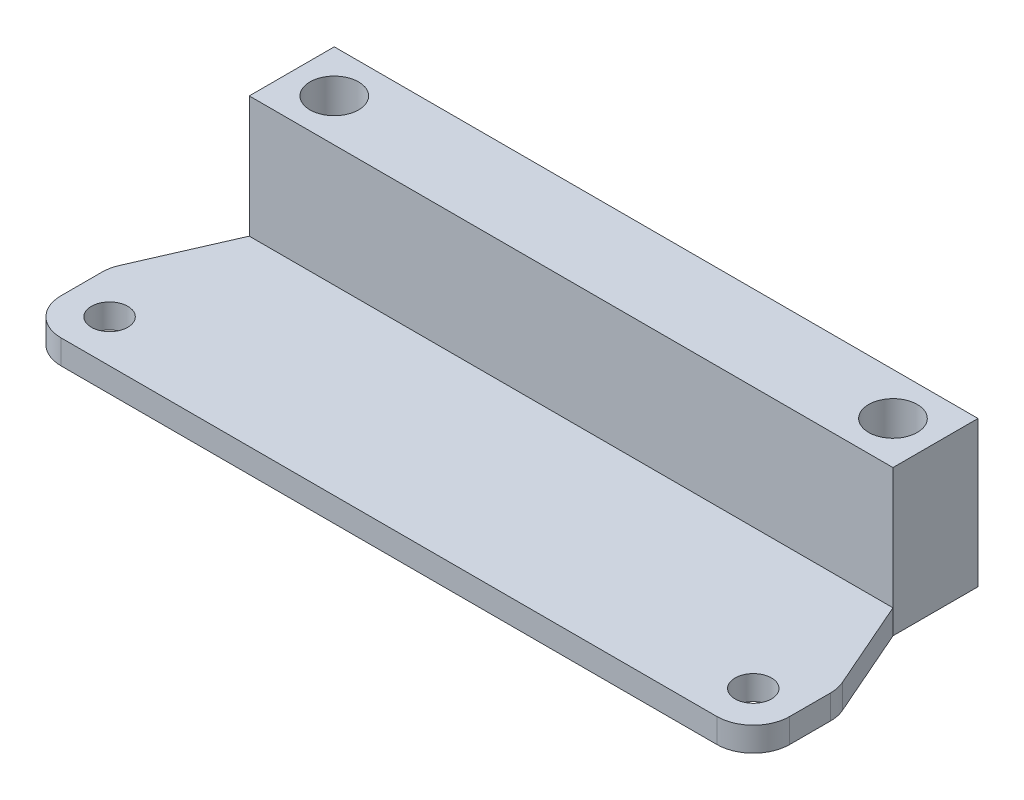
SolidWorks part; units mm, degrees
ref_plane "Front Plane" through (0, 0, 0) normal (0, 0, 1) x (1, 0, 0)
ref_plane "Top Plane" through (0, 0, 0) normal (0, 1, 0) x (1, 0, 0)
ref_plane "Right Plane" through (0, 0, 0) normal (1, 0, 0) x (0, 0, -1)
sketch "Sketch1" plane through (0, 0, 0) normal (0, 1, 0) x (1, 0, 0)
  line L0 (0.2515, 7.5749) -> (3.5, 15)
  line L17 (3.5, 15) -> (56.5, 15)
  line L18 (3.5, 15) -> (3.5, 22)
  line L19 (3.5, 22) -> (56.5, 22)
  line L20 (56.5, 15) -> (56.5, 22)
  line L21 (3, 0) -> (57, 0)
  line L22 (0, 3) -> (0, 6.3725)
  line L23 (0, 7) -> (60, 7)
  line L24 (60, 3) -> (60, 6.3725)
  line L25 (56.5, 15) -> (59.7485, 7.5749)
  arc A0 (60, 3) -> (57, 0) centre (57, 3) cw
  arc A1 (0, 3) -> (3, 0) centre (3, 3) ccw
  arc A2 (60, 6.3725) -> (59.7485, 7.5749) centre (57, 6.3725) ccw
  arc A3 (0, 6.3725) -> (0.2515, 7.5749) centre (3, 6.3725) cw
  point P1 (30, 7)
  point P2 (30, 15)
  point P10 (60, 0)
  point P15 (0, 0)
  point P16 (0, 0)
  dimension "D6" = 3
  dimension "D7" = 3
  dimension "D1" = 60
  dimension "D2" = 8
  dimension "D3" = 7
  dimension "D4" = 7
  dimension "D5" = 53
extrude "Boss-Extrude1" add sketch "Sketch1" along normal blind 2 contours L17 L20 L19 L18 | L25 L17 L0 L23 | L21 L24 L23 L22
sketch "Sketch2" plane through (0, 2, 0) normal (0, 1, 0) x (1, 0, 0)
  line L0 (0, 3) -> (0, 6.3725) construction
  line L1 (3, 0) -> (57, 0) construction
  line L2 (60, 3) -> (60, 6.3725) construction
  circle A0 centre (3.5, 3.5) radius 1.5
  circle A1 centre (56.5, 3.5) radius 1.5
  dimension "D1" = 3
  dimension "D2" = 3
  dimension "D3" = 3.5
  dimension "D4" = 3.5
  dimension "D6" = 3.5
  dimension "D5" = 3.5
extrude "Cut-Extrude1" cut sketch "Sketch2" against normal blind 2
sketch "Sketch3" plane through (0, 2, 0) normal (0, 1, 0) x (1, 0, 0)
  line L1 (3.5, 22) -> (56.5, 22)
  line L2 (3.5, 22) -> (3.5, 15)
  line L3 (3.5, 15) -> (56.5, 15)
  line L4 (56.5, 22) -> (56.5, 15)
extrude "Boss-Extrude2" add sketch "Sketch3" along normal blind 10
sketch "Sketch4" plane through (0, 12, 0) normal (0, 1, 0) x (1, 0, 0)
  line L0 (3.5, 22) -> (3.5, 15) construction
  line L1 (56.5, 15) -> (56.5, 22) construction
  line L2 (56.5, 22) -> (3.5, 22) construction
  circle A0 centre (7, 18.5) radius 2
  circle A1 centre (53, 18.5) radius 2
  dimension "D1" = 4
  dimension "D2" = 4
  dimension "D3" = 3.5
  dimension "D4" = 3.5
  dimension "D5" = 3.5
  dimension "D6" = 3.5
extrude "Cut-Extrude2" cut sketch "Sketch4" against normal blind 3.5
